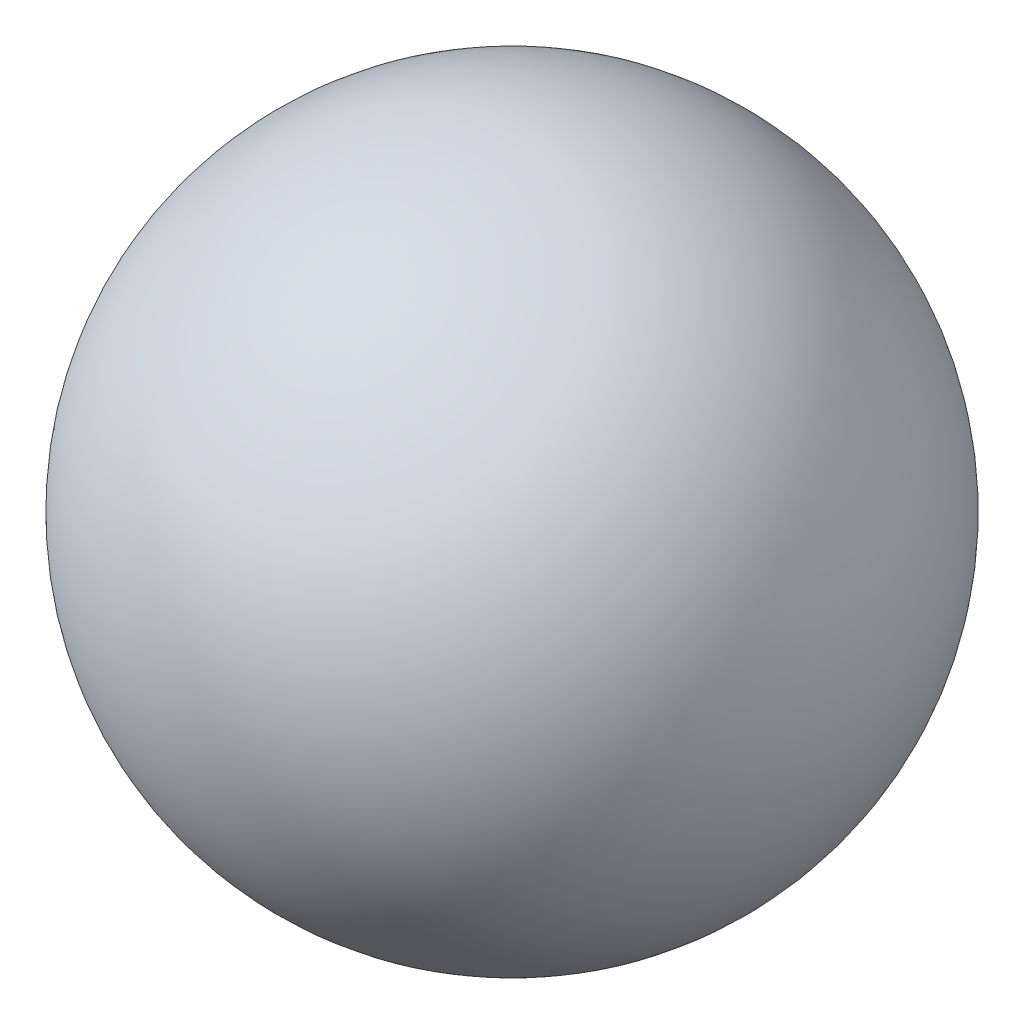
SolidWorks part; units mm, degrees
ref_plane "Front Plane" through (0, 0, 0) normal (0, 0, 1) x (1, 0, 0)
ref_plane "Top Plane" through (0, 0, 0) normal (0, 1, 0) x (1, 0, 0)
ref_plane "Right Plane" through (0, 0, 0) normal (1, 0, 0) x (0, 0, -1)
sketch "Sketch1" plane through (0, 0, 0) normal (0, 0, 1) x (1, 0, 0)
  line L0 (0, 21.335) -> (0, -21.335)
  arc A0 (0, 21.335) -> (0, -21.335) centre (0, 0) cw
  dimension "D1" = 42.67
revolve "Revolve1" add sketch "Sketch1" angle 360 about L0
